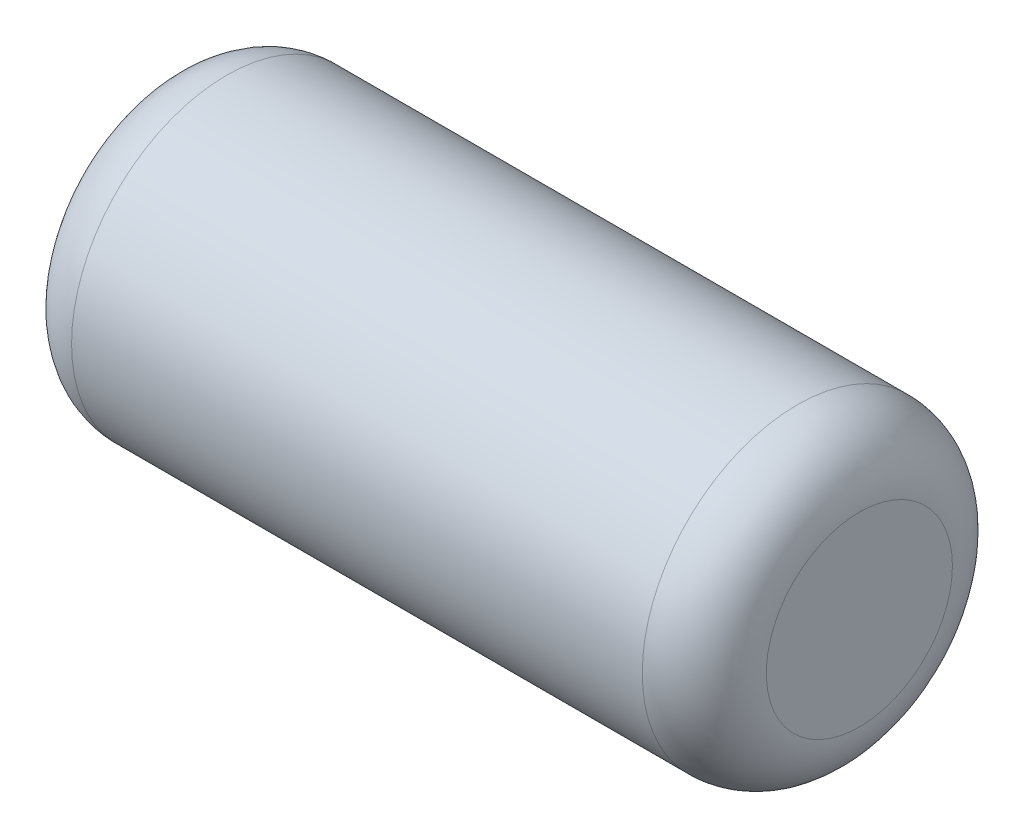
SolidWorks part; units mm, degrees
ref_plane "Front Plane" through (0, 0, 0) normal (0, 0, 1) x (1, 0, 0)
ref_plane "Top Plane" through (0, 0, 0) normal (0, 1, 0) x (1, 0, 0)
ref_plane "Right Plane" through (0, 0, 0) normal (1, 0, 0) x (0, 0, -1)
sketch "Sketch1" plane through (0, 0, 0) normal (1, 0, 0) x (0, 0, -1)
  circle A0 centre (0, 0) radius 63.5
  dimension "D1" = 127
extrude "Boss-Extrude1" add sketch "Sketch1" along normal blind 284.48
fillet "Fillet1" radius 25.4 2 edges at (284.48, 0, -63.5) (0, 0, -63.5)
